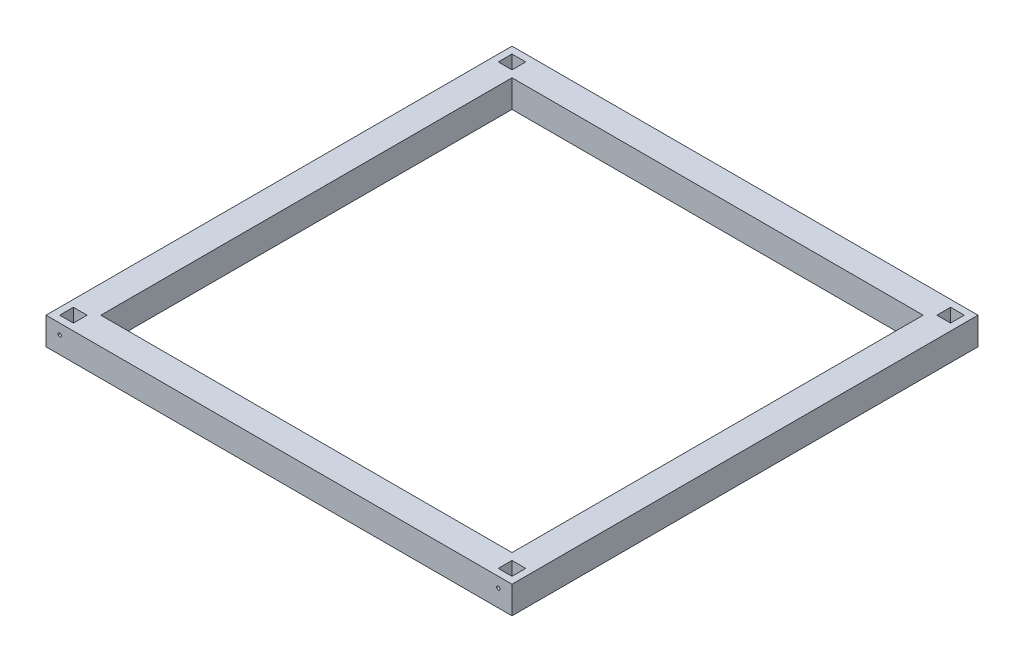
SolidWorks part; units mm, degrees
ref_plane "Front Plane" through (0, 0, 0) normal (0, 0, 1) x (1, 0, 0)
ref_plane "Top Plane" through (0, 0, 0) normal (0, 1, 0) x (1, 0, 0)
ref_plane "Right Plane" through (0, 0, 0) normal (1, 0, 0) x (0, 0, -1)
sketch "Sketch1" plane through (0, 0, 0) normal (0, 1, 0) x (1, 0, 0)
  line L0 (-340, 340) -> (340, 340)
  line L1 (-300, 300) -> (300, 300)
  line L2 (-300, 300) -> (-300, -300)
  line L3 (-300, -300) -> (300, -300)
  line L4 (300, 300) -> (300, -300)
  line L5 (-300, 300) -> (300, -300) construction
  line L6 (-300, -300) -> (300, 300) construction
  line L7 (340, 340) -> (340, -340)
  line L8 (-340, -340) -> (340, -340)
  line L9 (-340, 340) -> (-340, -340)
  point P0 (0, 0)
  point P6 (0, 0)
  dimension "D1" = 600
  dimension "D2" = 600
  dimension "D3" = 40
extrude "Boss-Extrude1" add sketch "Sketch1" along normal blind 40
sketch "Sketch2" plane through (0, 40, 0) normal (0, 1, 0) x (1, 0, 0)
  line L0 (340, 340) -> (-340, 340) construction
  line L5 (-330.0274, 330) -> (-310.0274, 330)
  line L6 (-330.0274, 330) -> (-330.0274, 310)
  line L7 (-330.0274, 310) -> (-310.0274, 310)
  line L8 (-310.0274, 330) -> (-310.0274, 310)
  line L9 (-330.0274, 330) -> (-310.0274, 310) construction
  line L10 (-330.0274, 310) -> (-310.0274, 330) construction
  line L11 (309.9726, 330) -> (309.9726, 310)
  line L12 (309.9726, 310) -> (329.9726, 310)
  line L13 (-340, 340) -> (-340, -340) construction
  line L14 (329.9726, 330) -> (329.9726, 310)
  line L15 (309.9726, 330) -> (329.9726, 330)
  line L16 (309.9726, -310) -> (309.9726, -330)
  line L17 (309.9726, -330) -> (329.9726, -330)
  line L18 (329.9726, -310) -> (329.9726, -330)
  line L19 (309.9726, -310) -> (329.9726, -310)
  line L20 (-330.0274, -310) -> (-330.0274, -330)
  line L21 (-330.0274, -330) -> (-310.0274, -330)
  line L22 (-310.0274, -310) -> (-310.0274, -330)
  line L23 (-330.0274, -310) -> (-310.0274, -310)
  line L24 (340, -340) -> (340, 340) construction
  line L25 (-340, -340) -> (340, -340) construction
  point P6 (-320.0274, 320)
  dimension "D1" = 20
  dimension "D2" = 20
  dimension "D3" = 20
  dimension "D4" = 19.9726
  dimension "D7" = 10.0274
  dimension "D8" = 10.0274
  dimension "D9" = 10
  dimension "D5" = 2
  dimension "D6" = 2
extrude "Cut-Extrude2" cut sketch "Sketch2" against normal blind 30
sketch "Sketch3" plane through (0, 0, -340) normal (0, 0, -1) x (-1, 0, 0)
  line L0 (-340, 40) -> (340, 40) construction
  line L1 (340, 40) -> (340, 0) construction
  line L2 (-340, 40) -> (-340, 0) construction
  circle A0 centre (320, 25) radius 2.5
  circle A1 centre (-320, 25) radius 2.5
  dimension "D1" = 5
  dimension "D2" = 15
  dimension "D3" = 20
  dimension "D5" = 20
  dimension "D4" = 2
extrude "Cut-Extrude3" cut sketch "Sketch3" against normal blind 40
sketch "Sketch4" plane through (0, 0, 340) normal (0, 0, 1) x (1, 0, 0)
  line L0 (-340, 40) -> (340, 40) construction
  line L3 (-340, 40) -> (-340, 0) construction
  line L4 (340, 40) -> (340, 0) construction
  circle A0 centre (-320, 25) radius 2.5
  circle A1 centre (320, 25) radius 2.5
  dimension "D1" = 5
  dimension "D4" = 2
  dimension "D2" = 15
  dimension "D3" = 20
  dimension "D5" = 20
extrude "Cut-Extrude4" cut sketch "Sketch4" against normal blind 40
